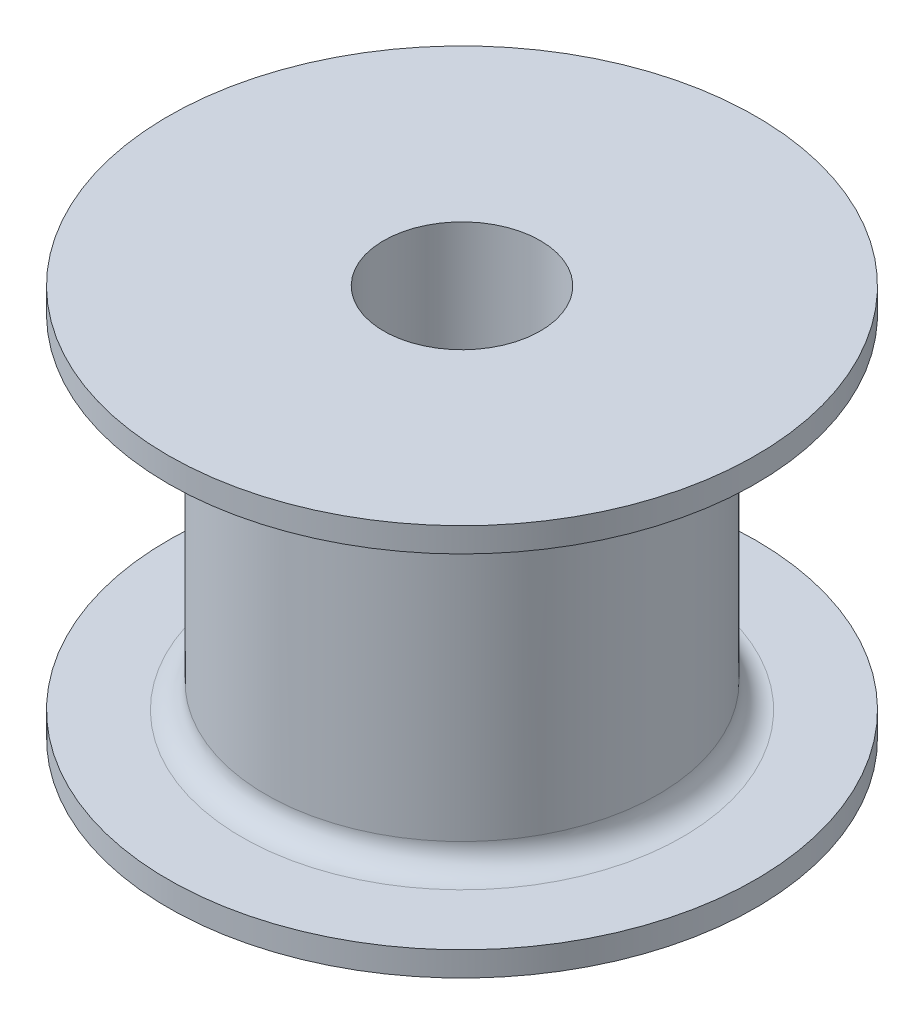
SolidWorks part; units mm, degrees
ref_plane "Front Plane" through (0, 0, 0) normal (0, 0, 1) x (1, 0, 0)
ref_plane "Top Plane" through (0, 0, 0) normal (0, 1, 0) x (1, 0, 0)
ref_plane "Right Plane" through (0, 0, 0) normal (1, 0, 0) x (0, 0, -1)
sketch "Sketch1" plane through (0, 0, 0) normal (0, 1, 0) x (1, 0, 0)
  circle A0 centre (0, 0) radius 4
  dimension "D1" = 8
extrude "Boss-Extrude1" add sketch "Sketch1" along normal blind 7
sketch "Sketch2" plane through (0, 7, 0) normal (0, 1, 0) x (1, 0, 0)
  circle A0 centre (0, 0) radius 6
  dimension "D1" = 12
extrude "Boss-Extrude2" add sketch "Sketch2" along normal blind 0.5
sketch "Sketch3" plane through (0, 0, 0) normal (0, -1, 0) x (1, 0, 0)
  circle A0 centre (0, 0) radius 6
  circle A1 centre (0, 0) radius 6 construction
extrude "Boss-Extrude3" add sketch "Sketch3" along normal blind 0.5
hole_wizard "M3 Clearance Hole1" positions "Sketch4" profile "Sketch5" hole size "M3" standard "ANSI Metric" end condition through all
sketch "Sketch4" plane through (0, -0.5, 0) normal (0, -1, 0) x (-1, 0, 0)
  point P0 (0, 0)
sketch "Sketch5" plane through (0, -0.5, 0) normal (1, 0, 0) x (0, 0, -1)
  line L0 (0, 0) -> (0, 8)
  line L1 (0, 8) -> (1.6, 8)
  line L2 (1.6, 8) -> (1.6, 0)
  line L5 (1.6, 0) -> (0, 0)
  line L11 (0, -6.35) -> (0, 107.95) construction
  dimension "Thru Hole Dia." = 3.2
  dimension "Thru Hole Depth" = 8
fillet "Fillet1" radius 0.5 2 edges at (0, 0, 4) (0, 7, 4)
